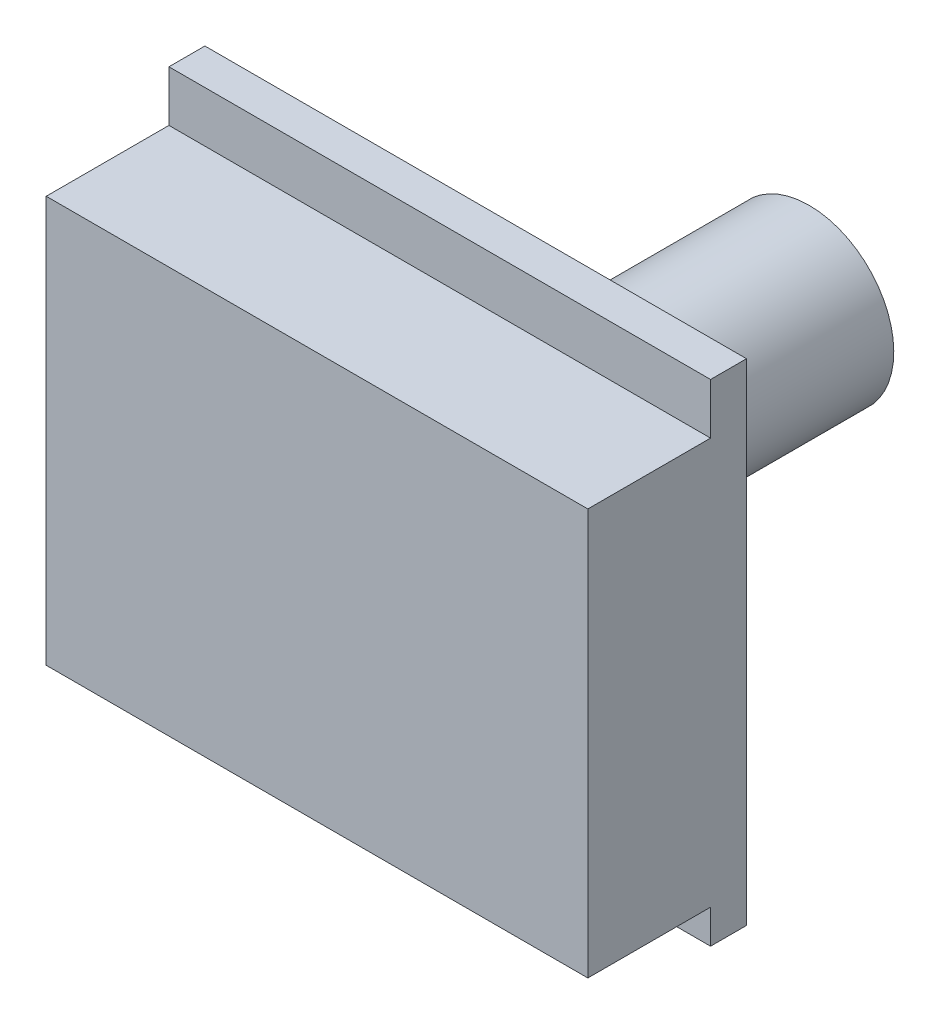
SolidWorks part; units mm, degrees
ref_plane "Piano frontale" through (0, 0, 0) normal (0, 0, 1) x (1, 0, 0)
ref_plane "Piano superiore" through (0, 0, 0) normal (0, 1, 0) x (1, 0, 0)
ref_plane "Piano destro" through (0, 0, 0) normal (1, 0, 0) x (0, 0, -1)
sketch "Schizzo1" plane through (0, 0, 0) normal (0, 0, 1) x (1, 0, 0)
  line L5 (-5.65, -4.05) -> (5.65, -4.05)
  line L6 (6.4, 4.8) -> (-6.4, 4.8)
  line L7 (6.4, 4.8) -> (6.4, -4.8)
  line L8 (6.4, -4.8) -> (-6.4, -4.8)
  line L9 (-6.4, 4.8) -> (-6.4, -4.8)
  line L10 (6.4, 4.8) -> (-6.4, -4.8) construction
  line L11 (6.4, -4.8) -> (-6.4, 4.8) construction
  line L12 (-5.65, -4.05) -> (-5.65, 4.05)
  line L13 (-5.65, 4.05) -> (5.65, 4.05)
  line L14 (5.65, -4.05) -> (5.65, 4.05)
  line L15 (-5.65, -4.05) -> (5.65, 4.05) construction
  line L16 (-5.65, 4.05) -> (5.65, -4.05) construction
  point P0 (0, 0)
  point P5 (0, 0)
  point P6 (0, 0)
  dimension "D1" = 12.8
  dimension "D2" = 0.75
  dimension "D3" = 0.75
  dimension "D4" = 9.6
extrude "Estrusione-Estrusione1" add sketch "Schizzo1" along normal blind 3
sketch "Schizzo2" plane through (0, 0, 3) normal (0, 0, 1) x (1, 0, 0)
  line L1 (-6.4, 4.8) -> (6.4, 4.8)
  line L2 (-6.4, 4.8) -> (-6.4, -4.8)
  line L3 (-6.4, -4.8) -> (6.4, -4.8)
  line L4 (6.4, 4.8) -> (6.4, -4.8)
extrude "Estrusione-Estrusione2" add sketch "Schizzo2" along normal blind 0.75
sketch "Schizzo3" plane through (0, 0, 0) normal (0, 0, -1) x (-1, 0, 0)
  line L0 (-6.4, -4.8) -> (-6.4, 4.8) construction
  line L1 (6.4, 4.8) -> (-6.4, 4.8)
  line L2 (6.4, 4.8) -> (6.4, 6)
  line L3 (6.4, 6) -> (-6.4, 6)
  line L4 (-6.4, 4.8) -> (-6.4, 6)
  line L5 (6.4, -4.8) -> (-6.4, -4.8)
  line L6 (6.4, -4.8) -> (6.4, -5.6)
  line L7 (6.4, -5.6) -> (-6.4, -5.6)
  line L8 (-6.4, -4.8) -> (-6.4, -5.6)
  dimension "D1" = 1.2
  dimension "D2" = 0.8
extrude "Estrusione-Estrusione3" add sketch "Schizzo3" against normal blind 0.85
sketch "Schizzo4" plane through (0, 0, 3) normal (0, 0, -1) x (-1, 0, 0)
  line L0 (5.65, 0.5) -> (1.9365, 0.5)
  line L1 (5.65, 4.05) -> (5.65, -4.05) construction
  line L2 (5.65, -0.5) -> (1.9365, -0.5)
  line L3 (-5.65, -4.05) -> (-5.65, 4.05) construction
  line L4 (5.65, 0.5) -> (1.9365, 0.5)
  line L5 (5.65, -0.5) -> (1.9365, -0.5)
  line L6 (-0.5, 1.9365) -> (-0.5, 4.05)
  line L7 (-5.65, -0.5) -> (-1.9365, -0.5)
  line L8 (-5.65, 0.5) -> (-1.9365, 0.5)
  line L9 (-5.65, 4.05) -> (5.65, 4.05) construction
  line L10 (-0.5, 4.05) -> (0.5, 4.05)
  line L11 (-5.65, 4.05) -> (5.65, 4.05) construction
  line L12 (0.5, 4.05) -> (0.5, 1.9365)
  line L13 (5.65, 0.5) -> (5.65, -0.5)
  line L14 (0.5, -1.9365) -> (0.5, -4.05)
  line L15 (5.65, -4.05) -> (-5.65, -4.05) construction
  line L16 (-0.5, -1.9365) -> (-0.5, -4.05)
  line L17 (-0.5, -4.05) -> (0.5, -4.05)
  line L18 (-5.65, -0.5) -> (-5.65, 0.5)
  arc A0 (-1.9365, 0.5) -> (-0.5, 1.9365) centre (0, 0) cw
  arc A2 (0.5, 1.9365) -> (1.9365, 0.5) centre (0, 0) cw
  arc A3 (-1.9365, -0.5) -> (-0.5, -1.9365) centre (0, 0) ccw
  arc A4 (0.5, -1.9365) -> (1.9365, -0.5) centre (0, 0) ccw
  line M14 (-5.65, 4.05) -> (-5.65, -4.05)
  line M15 (-5.65, -4.05) -> (5.65, -4.05)
  line M16 (5.65, -4.05) -> (5.65, 4.05)
  line M17 (5.65, 4.05) -> (-5.65, 4.05)
  dimension "D1" = 2
  dimension "D2" = 0.5
  dimension "D3" = 0.5
  dimension "D4" = 0.5
  dimension "D5" = 0.5
extrude "Estrusione-Estrusione4" add sketch "Schizzo4" along normal through all separate body contours L14 A4 L2 L0 A2 L12 L6 A0 L8 L7 A3 L16 M16 M17 M14 M15
sketch "Schizzo5" plane through (0, 0, 0) normal (0, 0, -1) x (-1, 0, 0)
  circle A0 centre (0, 0) radius 2
  dimension "D1" = 4
extrude "Estrusione-Estrusione5" add sketch "Schizzo5" along normal blind 7.88
